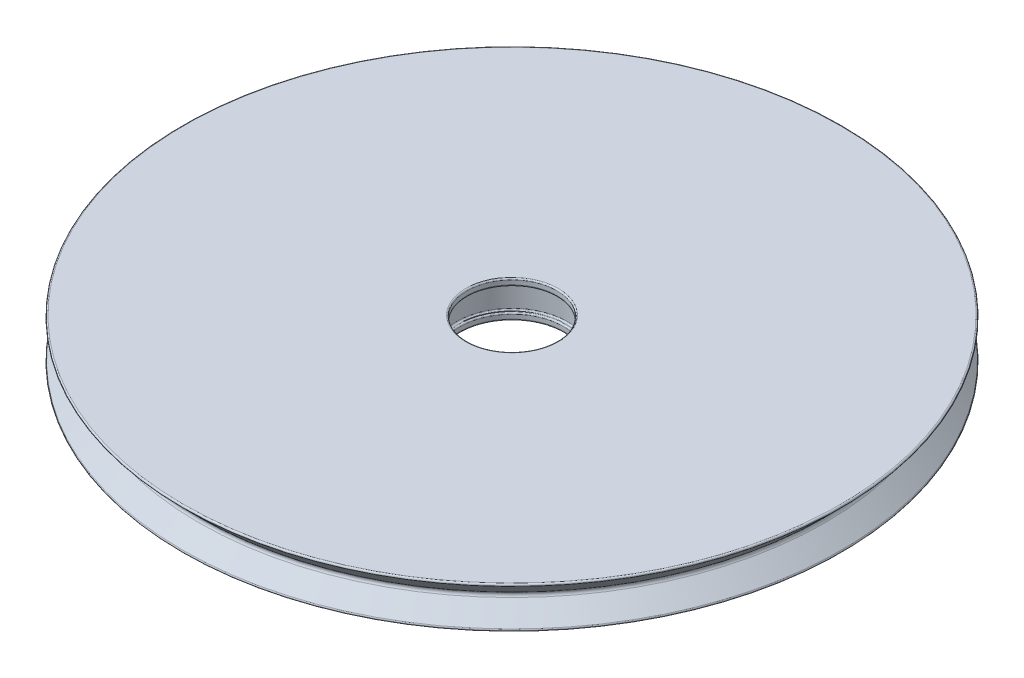
SolidWorks part; units mm, degrees
material "ABS"
ref_plane "Front" through (0, 0, 0) normal (0, 0, 1) x (1, 0, 0)
ref_plane "Top" through (0, 0, 0) normal (0, 1, 0) x (1, 0, 0)
ref_plane "Right" through (0, 0, 0) normal (1, 0, 0) x (0, 0, -1)
sketch "Esquisse1" plane through (0, 0, 0) normal (0, 0, 1) x (1, 0, 0)
  line L0 (6.5, 3) -> (48, 3)
  line L1 (6.5, 3) -> (6.5, 2)
  line L2 (8, 0) -> (45, 0) construction
  line L3 (45, 0) -> (48, 3)
  line L4 (0, 3) -> (0, -3) construction
  line L5 (6.5, 2) -> (8, 2)
  line L8 (8, 2) -> (8, -2)
  line L9 (7.5, -2) -> (8, -2)
  line L10 (45, 0) -> (48, -3)
  line L11 (7.5, -3) -> (7.5, -2)
  line L12 (7.5, -3) -> (48, -3)
  point P13 (0, 0)
  dimension "D1" = 0.5
  dimension "D2" = 1.5
  dimension "D3" = 16
  dimension "D4" = 4
  dimension "D5" = 6
  dimension "D6" = 90
revolve "Révolution1" add sketch "Esquisse1" angle 360 about L4
fillet "Congé1" radius 0.2 8 edges at (0, 2, 6.5) (0, -2, 8) (0, 2, 8) (0, 3, 6.5) (0, -3, 48) (0, 3, 48) (0, -3, 7.5) (0, -2, 7.5)
fillet "Congé2" radius 0.5 1 edges at (0, 0, 45)
sketch "Esquisse2" plane through (0, 0, 0) normal (0, 0, 1) x (1, 0, 0)
  line L0 (40, 2.8) -> (41.5, 2.8)
  line L1 (41.5, 2.8) -> (41.5, 0.3)
  line L2 (41.5, 0.3) -> (43, 0.3)
  line L3 (43, 0.3) -> (43, -3)
  line L4 (43, -3) -> (40, -3)
  line L5 (40, -3) -> (40, 2.8)
  line L6 (40, 2.8) -> (40, 5.3) construction
  line L8 (-47.5172, -3) -> (47.5172, -3) construction
  line L10 (47.5172, 3) -> (-47.5172, 3) construction
  point P7 (0, 0)
  point P8 (0, 0)
  point P9 (40, 2.1242)
  point P11 (14.3198, 0)
  point P12 (0, 0)
  point P13 (0, 0)
  point P17 (0, 0)
  dimension "D1" = 2.5
  dimension "D2" = 3
  dimension "D3" = 6
  dimension "D4" = 40
  dimension "D5" = 0.2
revolve "Enlèvement de matière-Révolution1" cut sketch "Esquisse2" angle 360 about L6
pattern_circular "Répétition circulaire1" count 3 over 360 about axis through (0, 0, 0) along (0, 1, 0) of "Enlèvement de matière-Révolution1"
sketch "Esquisse3" plane through (0, 0, 0) normal (0, 0, 1) x (1, 0, 0)
  line L0 (47.5172, 3) -> (-47.5172, 3) construction
  line L1 (10, -3) -> (43.7574, -3)
  line L2 (10, -3) -> (10, -1.7)
  line L3 (12, 0.3) -> (39.6289, 0.3)
  line L4 (43.7574, -3) -> (41.0431, -0.2858)
  line L5 (-47.5172, -3) -> (47.5172, -3) construction
  line L6 (47.6586, -2.6586) -> (45.3536, -0.3536) construction
  line L7 (0, -3) -> (0, 3) construction
  line L8 (37, 0.3) -> (43, 0.3) construction
  arc A0 (39.6289, 0.3) -> (41.0431, -0.2858) centre (39.6289, -1.7) cw
  arc A1 (10, -1.7) -> (12, 0.3) centre (12, -1.7) cw
  dimension "D2" = 2
  dimension "D1" = 2.7
  dimension "D3" = 3
  dimension "D4" = 10
revolve "Enlèvement de matière-Révolution2" cut sketch "Esquisse3" angle 360 about L7
